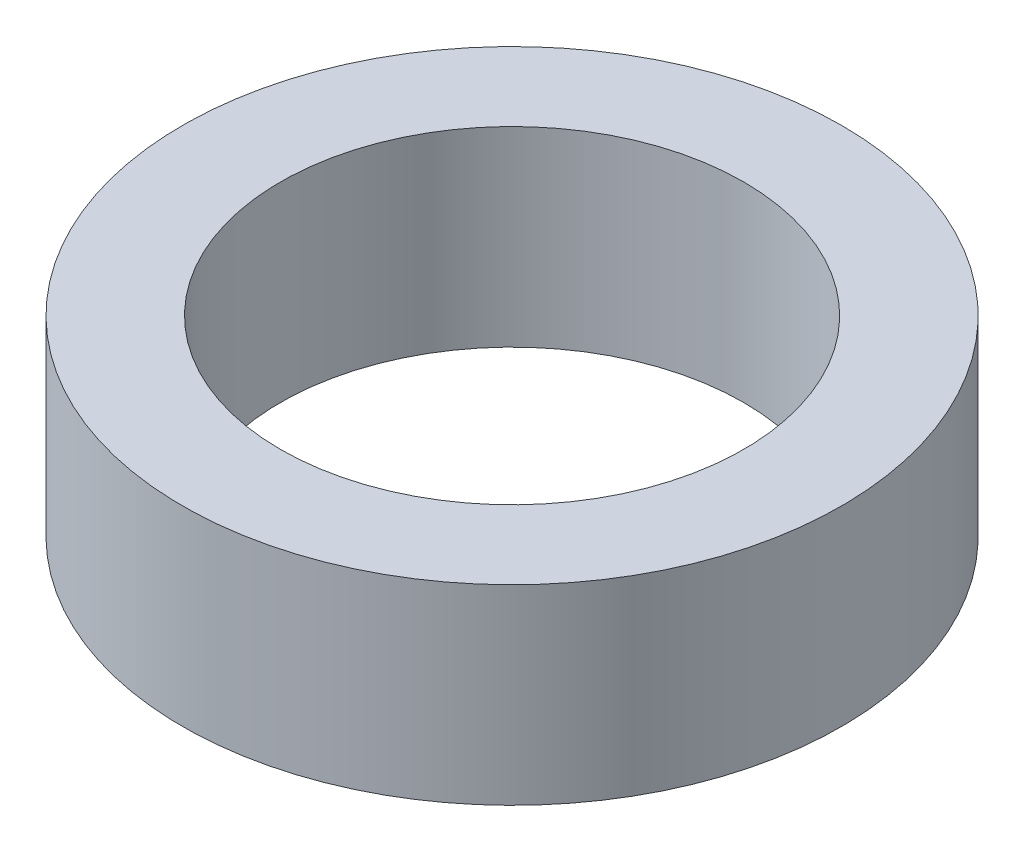
SolidWorks part; units mm, degrees
material "HDPE"
ref_plane "Piano frontale" through (0, 0, 0) normal (0, 0, 1) x (1, 0, 0)
ref_plane "Piano superiore" through (0, 0, 0) normal (0, 1, 0) x (1, 0, 0)
ref_plane "Piano destro" through (0, 0, 0) normal (1, 0, 0) x (0, 0, -1)
sketch "Schizzo1" plane through (0, 0, 0) normal (0, 0, 1) x (1, 0, 0)
  line L0 (-69, 40) -> (-48.5, 40)
  line L1 (-48.5, 40) -> (-48.5, 0)
  line L2 (-48.5, 0) -> (-69, 0)
  line L3 (-69, 0) -> (-69, 40)
  line L4 (0, 0) -> (0, 44.9066) construction
  dimension "D1" = 138
  dimension "D2" = 97
  dimension "D3" = 40
revolve "Rivoluzione1" add sketch "Schizzo1" angle 360 about L4
